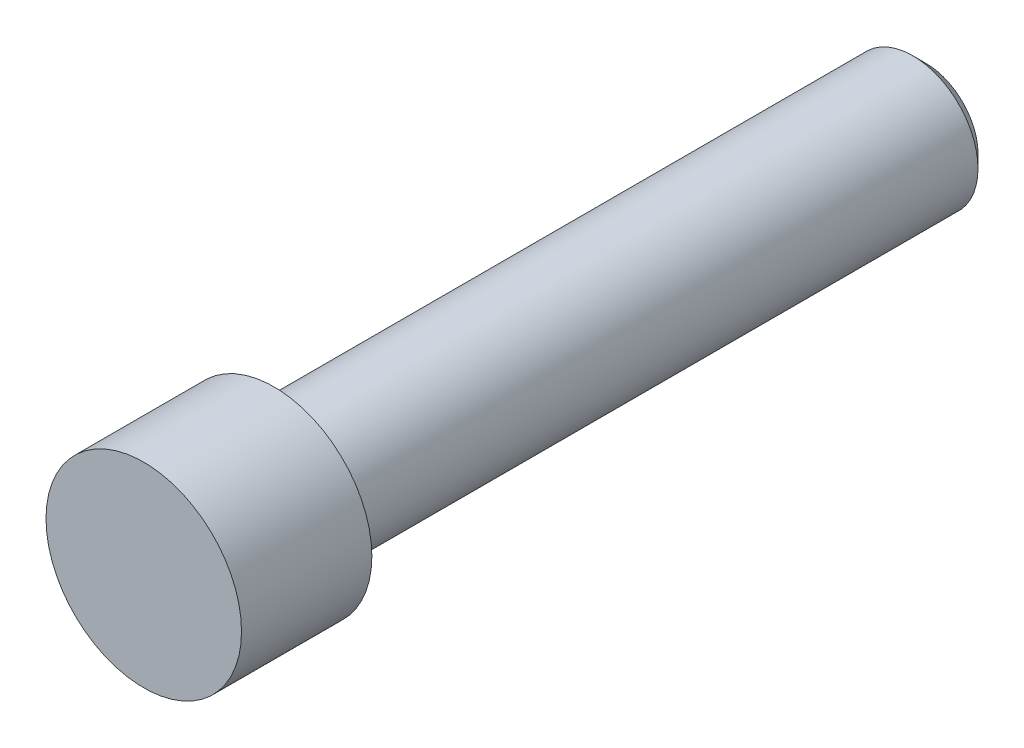
SolidWorks part; units mm, degrees
ref_plane "Alzado" through (0, 0, 0) normal (0, 0, 1) x (1, 0, 0)
ref_plane "Planta" through (0, 0, 0) normal (0, 1, 0) x (1, 0, 0)
ref_plane "Vista lateral" through (0, 0, 0) normal (1, 0, 0) x (0, 0, -1)
sketch "Croquis1" plane through (0, 0, 0) normal (0, 0, 1) x (1, 0, 0)
  circle A0 centre (0, 0) radius 1
  dimension "D1" = 2
extrude "Saliente-Extruir1" add sketch "Croquis1" along normal blind 10
chamfer "Chaflán1" distance 0.2 angle 45 1 edges at (1, 0, 0)
sketch "Croquis2" plane through (0, 0, 10) normal (0, 0, 1) x (1, 0, 0)
  circle A0 centre (0, 0) radius 1.5
  dimension "D1" = 3
extrude "Saliente-Extruir2" add sketch "Croquis2" along normal blind 2
